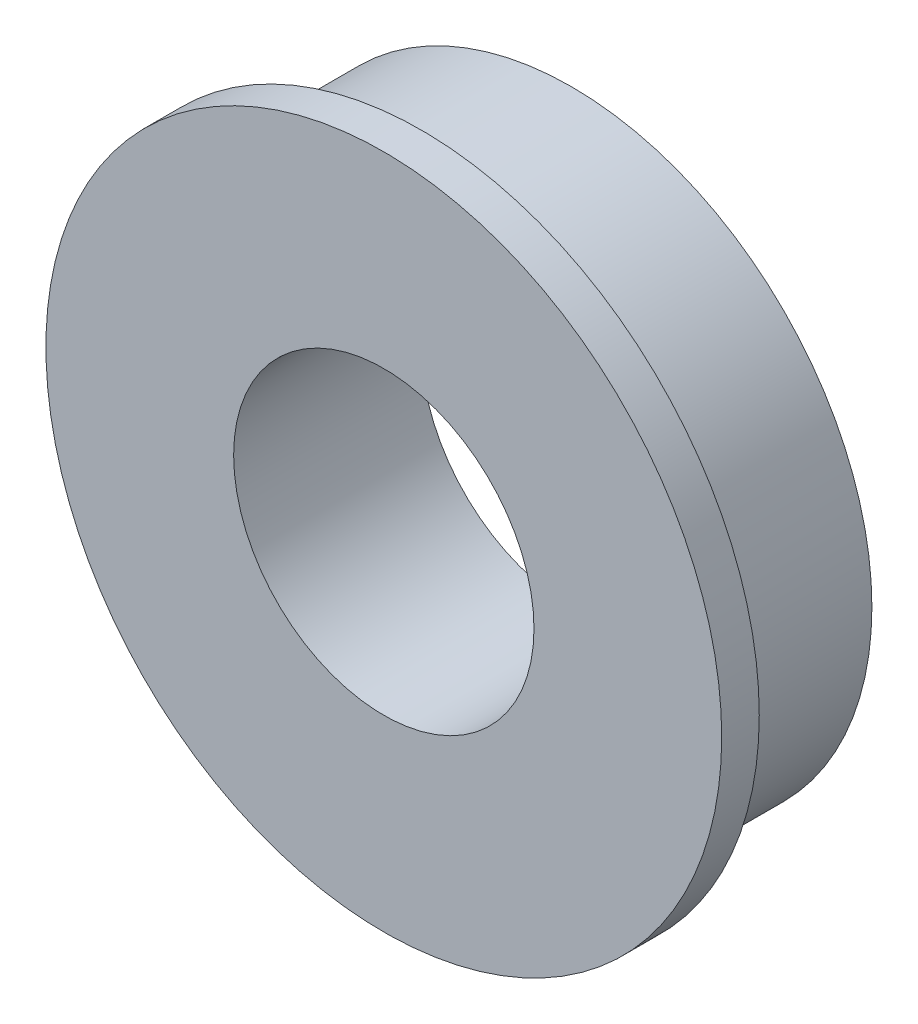
SolidWorks part; units mm, degrees
material "1023 Carbon Steel Sheet (SS)"
ref_plane "Płaszczyzna przednia" through (0, 0, 0) normal (0, 0, 1) x (1, 0, 0)
ref_plane "Płaszczyzna górna" through (0, 0, 0) normal (0, 1, 0) x (1, 0, 0)
ref_plane "Płaszczyzna prawa" through (0, 0, 0) normal (1, 0, 0) x (0, 0, -1)
sketch "Sketch1" plane through (0, 0, 0) normal (0, 0, 1) x (1, 0, 0)
  circle A0 centre (0, 0) radius 8
  circle A1 centre (0, 0) radius 4
  dimension "D1" = 16
  dimension "D2" = 8
extrude "Boss-Extrude1" add sketch "Sketch1" along normal blind 5
sketch "Sketch2" plane through (0, 0, 5) normal (0, 0, 1) x (1, 0, 0)
  circle A0 centre (0, 0) radius 4 construction
  circle A1 centre (0, 0) radius 8
  circle A2 centre (0, 0) radius 8 construction
  circle A3 centre (0, 0) radius 4
  circle A4 centre (0, 0) radius 9
  dimension "D2" = 1
  dimension "D1" = 0
extrude "Boss-Extrude2" add sketch "Sketch2" against normal blind 1
